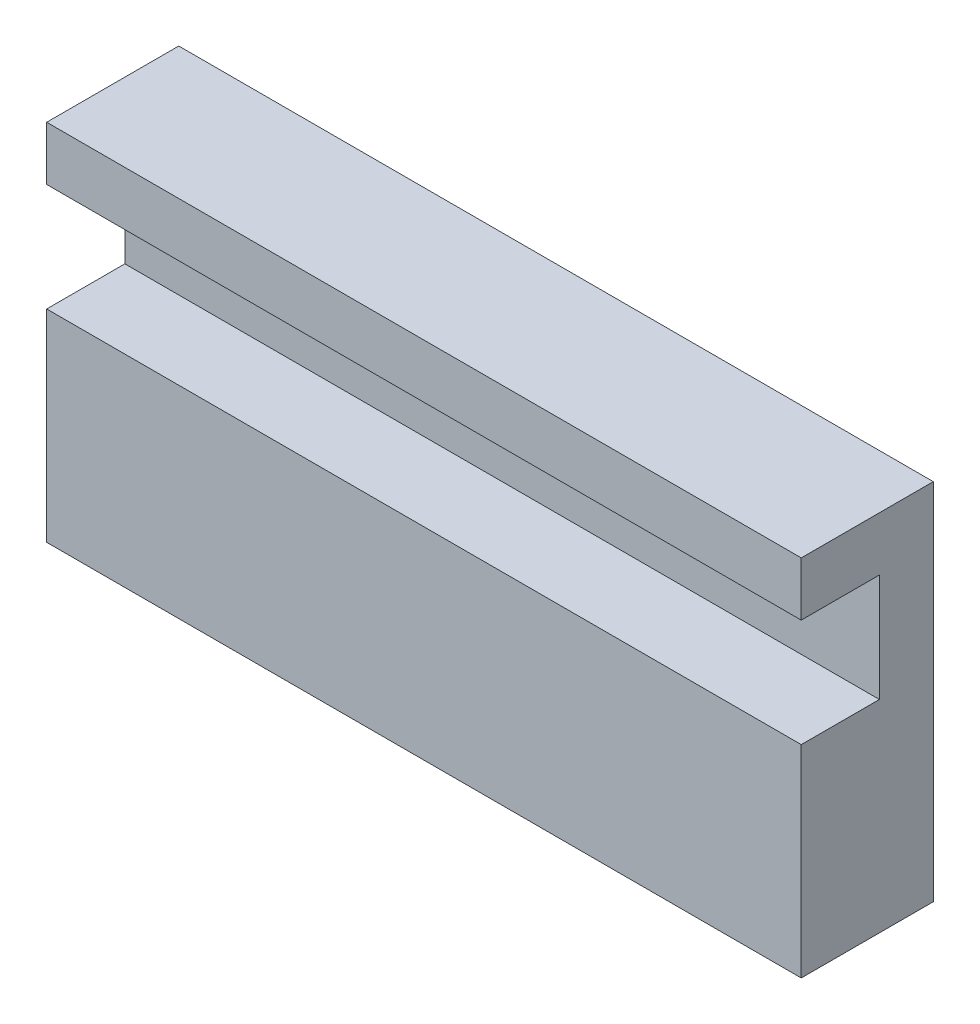
SolidWorks part; units mm, degrees
ref_plane "Front Plane" through (0, 0, 0) normal (0, 0, 1) x (1, 0, 0)
ref_plane "Top Plane" through (0, 0, 0) normal (0, 1, 0) x (1, 0, 0)
ref_plane "Right Plane" through (0, 0, 0) normal (1, 0, 0) x (0, 0, -1)
sketch "Sketch1" plane through (0, 0, 0) normal (0, 0, 1) x (1, 0, 0)
  line L1 (0, 0) -> (27.998, 0)
  line L2 (0, 0) -> (0, 15)
  line L3 (0, 15) -> (27.998, 15)
  line L4 (27.998, 0) -> (27.998, 15)
  dimension "D1" = 27.998
  dimension "D2" = 15
extrude "Boss-Extrude1" add sketch "Sketch1" along normal blind 4.9
sketch "Sketch3" plane through (0, 0, 0) normal (0, -1, 0) x (1, 0, 0)
  line L0 (5.656, 1.286) -> (2.746, 1.286) construction
  line L1 (2.746, 4.254) -> (2.746, 1.286) construction
  line L2 (5.656, 4.254) -> (2.746, 4.254) construction
  line L3 (5.656, 4.254) -> (5.656, 1.286) construction
  line L4 (23.784, 1.318) -> (20.876, 1.318) construction
  line L5 (20.876, 4.228) -> (20.876, 1.318) construction
  line L6 (23.784, 4.228) -> (23.784, 1.318) construction
  line L7 (20.876, 4.228) -> (23.784, 4.228) construction
  line L8 (5.656, 1.286) -> (2.746, 1.286)
  line L9 (2.746, 4.254) -> (2.746, 1.286)
  line L10 (5.656, 4.254) -> (2.746, 4.254)
  line L11 (5.656, 4.254) -> (5.656, 1.286)
  line L12 (23.784, 1.318) -> (20.876, 1.318)
  line L13 (20.876, 4.228) -> (20.876, 1.318)
  line L14 (23.784, 4.228) -> (23.784, 1.318)
  line L15 (20.876, 4.228) -> (23.784, 4.228)
  line L16 (24.034, 4.478) -> (24.034, 1.068)
  line L17 (24.034, 1.068) -> (20.626, 1.068)
  line L18 (20.626, 4.478) -> (20.626, 1.068)
  line L19 (20.626, 4.478) -> (24.034, 4.478)
  line L20 (5.906, 1.036) -> (2.496, 1.036)
  line L21 (2.496, 4.504) -> (2.496, 1.036)
  line L22 (5.906, 4.504) -> (2.496, 4.504)
  line L23 (5.906, 4.504) -> (5.906, 1.036)
  dimension "D1" = 0.25
extrude "Cut-Extrude1" cut sketch "Sketch3" against normal blind 5.5 contours L15 L13 L12 L14 | L19 L18 L17 L16 L13 L15 L14 L12 | L11 L10 L9 L8 | L23 L22 L21 L20 L10 L11 L8 L9
sketch "Sketch4" plane through (27.998, 0, 0) normal (1, 0, 0) x (0, 0, -1)
  line L0 (-4.9, 0) -> (-4.9, 15) construction
  line L1 (-4.9, 7.5) -> (-2, 7.5)
  line L2 (-4.9, 7.5) -> (-4.9, 11.5)
  line L3 (-4.9, 11.5) -> (-2, 11.5)
  line L4 (-2, 7.5) -> (-2, 11.5)
  line L5 (-4.478, 5.5) -> (-1.068, 5.5) construction
  line L7 (0, 0) -> (0, 15) construction
  dimension "D1" = 2
  dimension "D2" = 4
  dimension "D3" = 2
extrude "Cut-Extrude2" cut sketch "Sketch4" against normal blind 30.5
sketch "Sketch5" plane through (0, 15, 0) normal (0, 1, 0) x (1, 0, 0)
  line L1 (0, -4.9) -> (27.998, -4.9)
  line L2 (0, -4.9) -> (0, 0)
  line L3 (0, 0) -> (27.998, 0)
  line L4 (27.998, -4.9) -> (27.998, 0)
extrude "Cut-Extrude3" cut sketch "Sketch5" against normal blind 1.5
